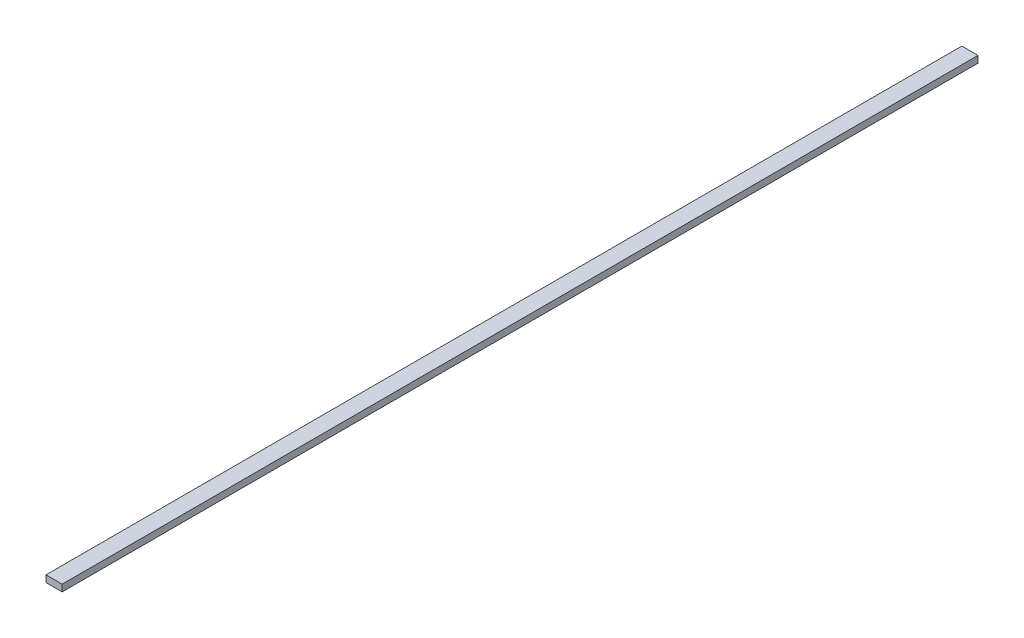
SolidWorks part; units mm, degrees
ref_plane "Ebene vorne" through (0, 0, 0) normal (0, 0, 1) x (1, 0, 0)
ref_plane "Ebene oben" through (0, 0, 0) normal (0, 1, 0) x (1, 0, 0)
ref_plane "Ebene rechts" through (0, 0, 0) normal (1, 0, 0) x (0, 0, -1)
sketch "Skizze1" plane through (0, 0, 0) normal (0, 0, 1) x (1, 0, 0)
  line L1 (0, 0) -> (12, 0)
  line L2 (0, 0) -> (0, 5)
  line L3 (0, 5) -> (12, 5)
  line L4 (12, 0) -> (12, 5)
  dimension "D1" = 5
  dimension "D2" = 12
extrude "Aufsatz-Linear austragen1" add sketch "Skizze1" along normal blind 680
